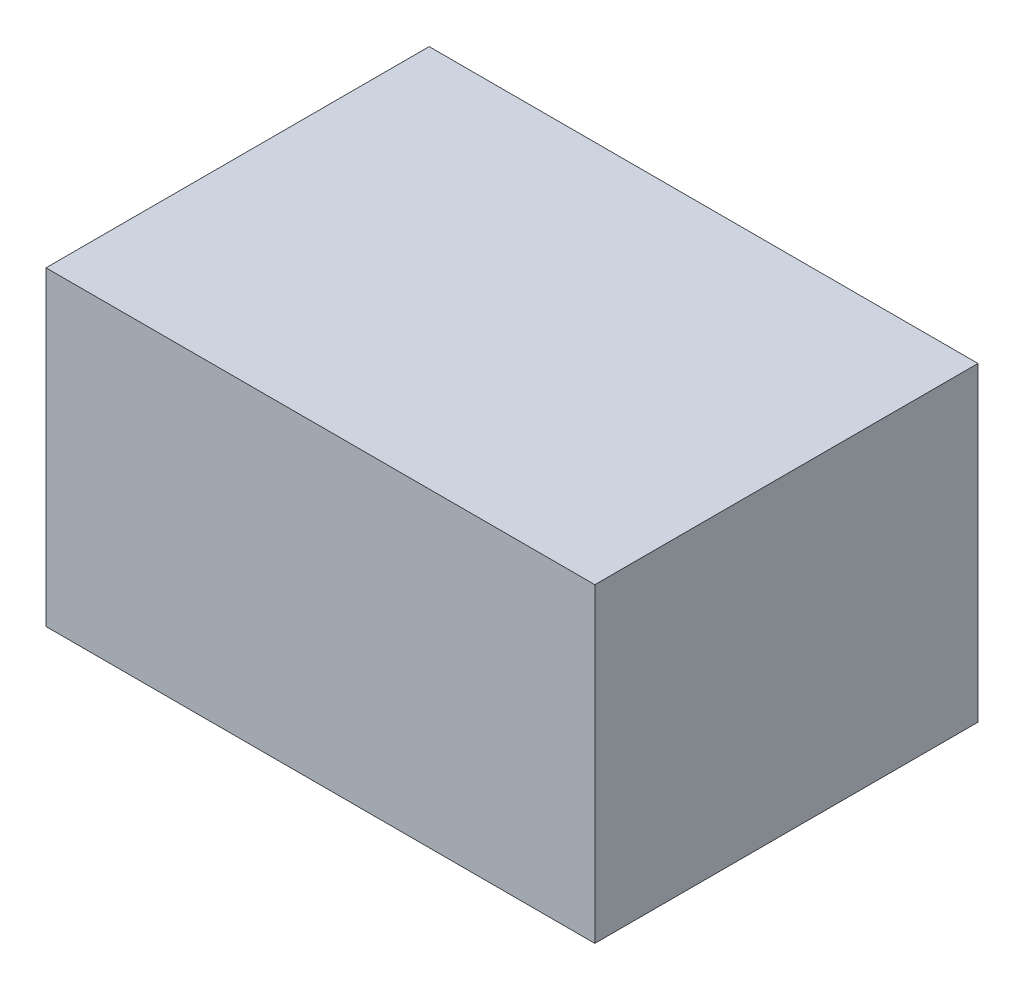
SolidWorks part; units mm, degrees
ref_plane "Front Plane" through (0, 0, 0) normal (0, 0, 1) x (1, 0, 0)
ref_plane "Top Plane" through (0, 0, 0) normal (0, 1, 0) x (1, 0, 0)
ref_plane "Right Plane" through (0, 0, 0) normal (1, 0, 0) x (0, 0, -1)
sketch "Sketch1" plane through (0, 0, 0) normal (0, 1, 0) x (1, 0, 0)
  line L1 (-132.5, -92.5) -> (132.5, -92.5)
  line L2 (-132.5, -92.5) -> (-132.5, 92.5)
  line L3 (-132.5, 92.5) -> (132.5, 92.5)
  line L4 (132.5, -92.5) -> (132.5, 92.5)
  line L5 (-132.5, -92.5) -> (132.5, 92.5) construction
  line L6 (-132.5, 92.5) -> (132.5, -92.5) construction
  point P0 (0, 0)
  dimension "D1" = 265
  dimension "D2" = 185
extrude "Boss-Extrude1" add sketch "Sketch1" along normal mid plane 150
